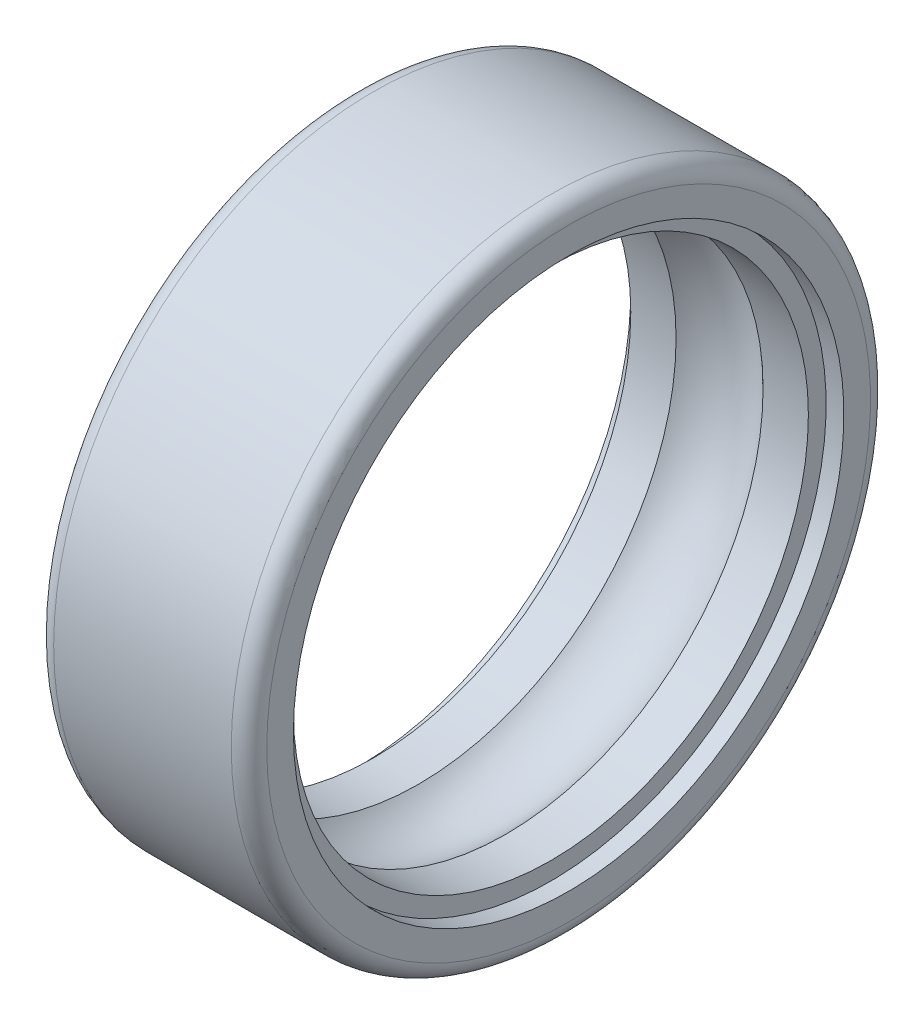
SolidWorks part; units mm, degrees
ref_plane "Front" through (0, 0, 0) normal (0, 0, 1) x (1, 0, 0)
ref_plane "Top" through (0, 0, 0) normal (0, 1, 0) x (1, 0, 0)
ref_plane "Right" through (0, 0, 0) normal (1, 0, 0) x (0, 0, -1)
sketch "Sketch1" plane through (0, 0, 0) normal (0, 0, 1) x (1, 0, 0)
  line L0 (-6, 6) -> (6, 6)
  line L1 (-6, 0) -> (6, 0)
  line L2 (-6, 0) -> (-6, 18)
  line L3 (-6, 18) -> (6, 18)
  line L4 (6, 0) -> (6, 18)
  line L5 (-6, 18) -> (6, 6)
  line L6 (-6, 14.5) -> (6, 14.5)
  line L7 (-6, 9.5) -> (6, 9.5)
  circle A0 centre (0, 12) radius 3.5
  dimension "D4" = 7
  dimension "D1" = 18
  dimension "D2" = 12
  dimension "D3" = 12
  dimension "D5" = 3.5
  dimension "D6" = 3.5
sketch "Sketch2" plane through (0, 0, 0) normal (0, 0, 1) x (1, 0, 0)
  line L0 (-6, 14.5) -> (6, 14.5) construction
  line L1 (-6, 14.5) -> (-2.4495, 14.5)
  line L2 (-6, 18) -> (6, 18) construction
  line L3 (-6, 0) -> (-6, 18) construction
  line L4 (6, 0) -> (6, 18) construction
  line L5 (-6, 0) -> (6, 0) construction
  line L6 (-5, 18) -> (5, 18)
  line L7 (-6, 14.5) -> (-6, 17)
  line L8 (6, 14.5) -> (6, 17)
  line L9 (-6, 0) -> (6, 0) construction
  line L10 (2.4495, 14.5) -> (6, 14.5)
  circle A0 centre (0, 12) radius 3.5 construction
  arc A1 (2.4495, 14.5) -> (-2.4495, 14.5) centre (0, 12) ccw
  arc A2 (5, 18) -> (6, 17) centre (5, 17) cw
  arc A3 (-5, 18) -> (-6, 17) centre (-5, 17) ccw
  dimension "D1" = 1
revolve "Revolve1" add sketch "Sketch2" angle 360 about L9
sketch "Sketch3" plane through (-6, 0, 0) normal (-1, 0, 0) x (0, 0, 1)
  circle A0 centre (0, 0) radius 14.5 construction
  circle A1 centre (0, 0) radius 14.5
  circle A2 centre (0, 0) radius 15.5
  dimension "D1" = 1
extrude "Cut-Extrude1" cut sketch "Sketch3" against normal blind 1
mirror "Mirror1" about plane through (0, 0, 0) normal (1, 0, 0) of "Cut-Extrude1"
sketch "Sketch4" plane through (-6, 0, 0) normal (-1, 0, 0) x (0, 0, 1)
  circle A0 centre (0, 0) radius 15.6 construction
  circle A1 centre (0, 0) radius 15.5 construction
  text T0 "6301 ZZ" font "Century Gothic" height in points 4
  text T1 "                                                                                                                                                                                                          KOYO  BEARING" font "Century Gothic" height in points 4
  dimension "D1" = 0.1
split line "Split Line1"
